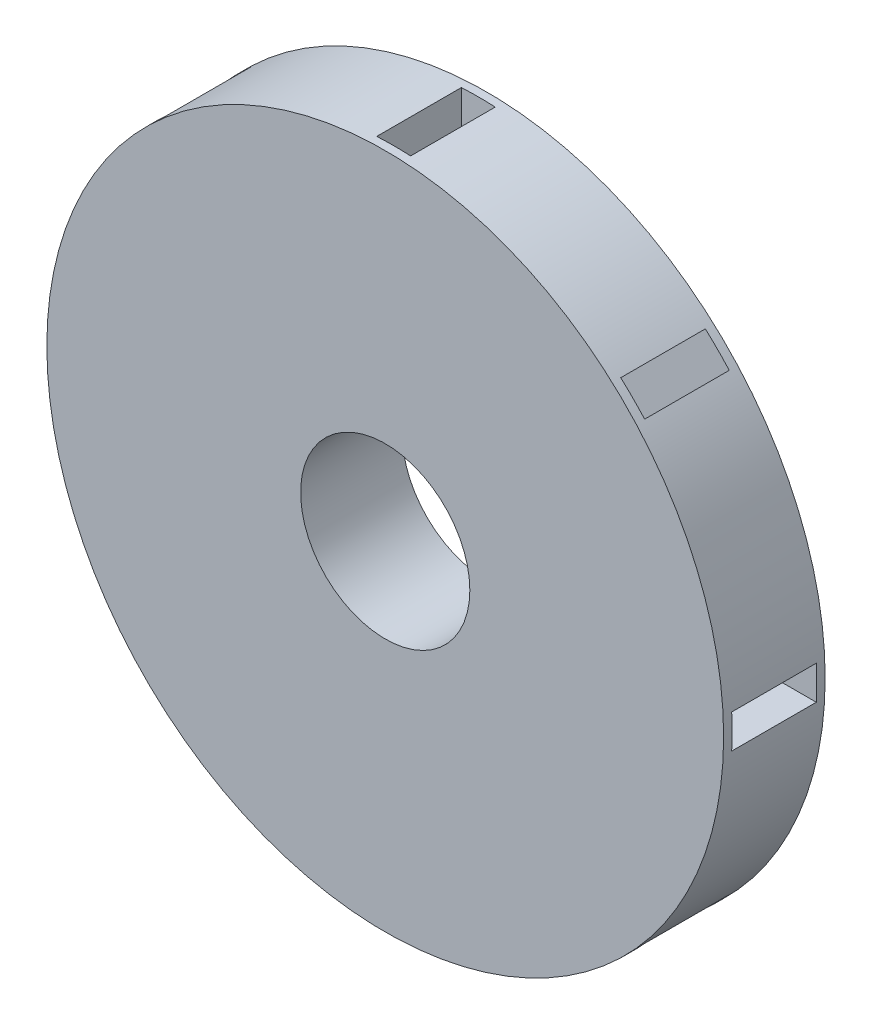
SolidWorks part; units mm, degrees
ref_plane "Front Plane" through (0, 0, 0) normal (0, 0, 1) x (1, 0, 0)
ref_plane "Top Plane" through (0, 0, 0) normal (0, 1, 0) x (1, 0, 0)
ref_plane "Right Plane" through (0, 0, 0) normal (1, 0, 0) x (0, 0, -1)
sketch "Sketch1" plane through (0, 0, 0) normal (0, 0, 1) x (1, 0, 0)
  circle A0 centre (0, 0) radius 100
  circle A1 centre (0, 0) radius 25
  dimension "D1" = 200
  dimension "D2" = 50
extrude "Boss-Extrude1" add sketch "Sketch1" along normal mid plane 30
sketch "Sketch2" plane through (0, 0, 0) normal (0, 0, 1) x (1, 0, 0)
  line L0 (-197.3542, 0) -> (197.3542, 0) construction
  line L1 (0, -134.9292) -> (0, 134.9292) construction
  line L2 (100, -104.4095) -> (100, 104.4095) construction
  line L3 (60, -86.1693) -> (60, 86.1693) construction
  line L4 (100, 5) -> (110, -5)
  line L5 (60, -5) -> (100, -5)
  line L6 (60, -5) -> (60, 5)
  line L7 (60, 5) -> (100, 5)
  line L8 (100, -5) -> (100, 5) construction
  line L9 (60, -5) -> (100, 5) construction
  line L10 (60, 5) -> (100, -5) construction
  line L11 (110, -5) -> (100, -5)
  line L12 (67.1751, -74.2462) -> (74.2462, -67.1751) construction
  line L13 (45.9619, -38.8909) -> (74.2462, -67.1751)
  line L14 (38.8909, -45.9619) -> (67.1751, -74.2462)
  line L15 (38.8909, -45.9619) -> (45.9619, -38.8909)
  line L16 (74.2462, -67.1751) -> (74.2462, -81.3173)
  line L17 (74.2462, -81.3173) -> (67.1751, -74.2462)
  line L18 (-5, -100) -> (5, -100) construction
  line L19 (5, -60) -> (5, -100)
  line L20 (-5, -60) -> (-5, -100)
  line L21 (-5, -60) -> (5, -60)
  line L22 (5, -100) -> (-5, -110)
  line L23 (-5, -110) -> (-5, -100)
  line L24 (-74.2462, -67.1751) -> (-67.1751, -74.2462) construction
  line L25 (-38.8909, -45.9619) -> (-67.1751, -74.2462)
  line L26 (-45.9619, -38.8909) -> (-74.2462, -67.1751)
  line L27 (-45.9619, -38.8909) -> (-38.8909, -45.9619)
  line L28 (-67.1751, -74.2462) -> (-81.3173, -74.2462)
  line L29 (-81.3173, -74.2462) -> (-74.2462, -67.1751)
  line L30 (-100, 5) -> (-100, -5) construction
  line L31 (-60, -5) -> (-100, -5)
  line L32 (-60, 5) -> (-100, 5)
  line L33 (-60, 5) -> (-60, -5)
  line L34 (-100, -5) -> (-110, 5)
  line L35 (-110, 5) -> (-100, 5)
  line L36 (-67.1751, 74.2462) -> (-74.2462, 67.1751) construction
  line L37 (-45.9619, 38.8909) -> (-74.2462, 67.1751)
  line L38 (-38.8909, 45.9619) -> (-67.1751, 74.2462)
  line L39 (-38.8909, 45.9619) -> (-45.9619, 38.8909)
  line L40 (-74.2462, 67.1751) -> (-74.2462, 81.3173)
  line L41 (-74.2462, 81.3173) -> (-67.1751, 74.2462)
  line L42 (5, 100) -> (-5, 100) construction
  line L43 (-5, 60) -> (-5, 100)
  line L44 (5, 60) -> (5, 100)
  line L45 (5, 60) -> (-5, 60)
  line L46 (-5, 100) -> (5, 110)
  line L47 (5, 110) -> (5, 100)
  line L48 (74.2462, 67.1751) -> (67.1751, 74.2462) construction
  line L49 (38.8909, 45.9619) -> (67.1751, 74.2462)
  line L50 (45.9619, 38.8909) -> (74.2462, 67.1751)
  line L51 (45.9619, 38.8909) -> (38.8909, 45.9619)
  line L52 (67.1751, 74.2462) -> (81.3173, 74.2462)
  line L53 (81.3173, 74.2462) -> (74.2462, 67.1751)
  point P0 (80, 0)
  point P4 (0, 0)
  point P8 (0, 0)
  point P11 (100, 0)
  point P14 (60, 0)
  point P22 (0, 0)
  point P28 (0, 0)
  point P34 (0, 0)
  point P40 (0, 0)
  point P46 (0, 0)
  point P52 (0, 0)
  point P58 (0, 0)
  point P64 (0, 0)
  dimension "D1" = 100
  dimension "D2" = 60
  dimension "D3" = 80
  dimension "D4" = 10
  dimension "D5" = 40
  dimension "D6" = 10
  dimension "D7" = 8
extrude "Cut-Extrude1" cut sketch "Sketch2" against normal mid plane 25
